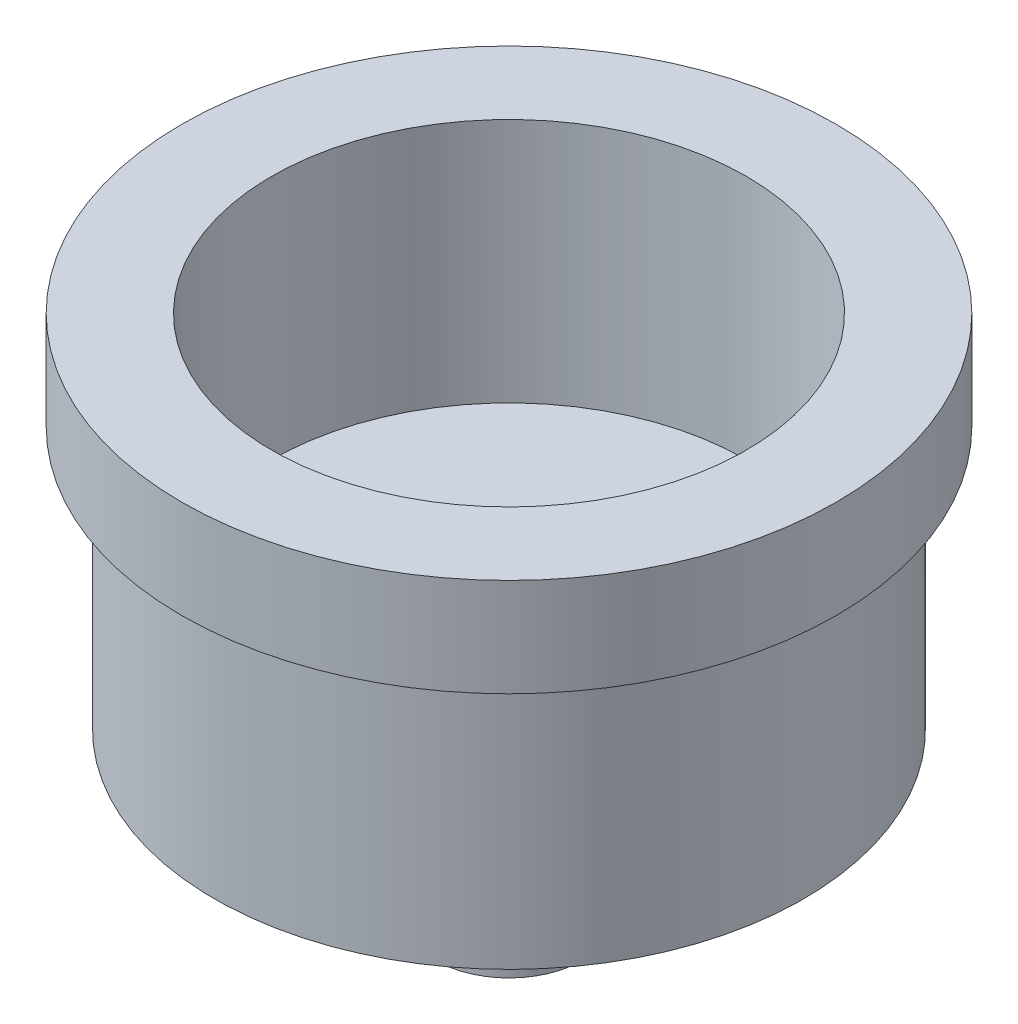
SolidWorks part; units mm, degrees
ref_plane "前视基准面" through (0, 0, 0) normal (0, 0, 1) x (1, 0, 0)
ref_plane "上视基准面" through (0, 0, 0) normal (0, 1, 0) x (1, 0, 0)
ref_plane "右视基准面" through (0, 0, 0) normal (1, 0, 0) x (0, 0, -1)
other "Configuration Table"
sketch "草图1" plane through (0, 0, 0) normal (0, 0, 1) x (1, 0, 0)
  line L0 (0, 0) -> (0, 32) construction
  line L1 (-20, 32) -> (-20, 26)
  line L2 (-20, 26) -> (-18, 26)
  line L3 (-18, 26) -> (-18, 10)
  line L4 (-18, 10) -> (-6.5, 10)
  line L5 (-6.5, 10) -> (-6.5, 9)
  line L6 (-6.5, 9) -> (-4.5, 9)
  line L7 (-4.5, 9) -> (-4.5, 0)
  line L8 (-4.5, 0) -> (-2.5, 0)
  line L9 (-2.5, 0) -> (-2.5, 13)
  line L10 (-2.5, 13) -> (-4.75, 13)
  line L11 (-4.75, 13) -> (-4.75, 17)
  line L12 (-4.75, 17) -> (-14.5, 17)
  line L13 (-14.5, 17) -> (-14.5, 32)
  line L14 (-14.5, 32) -> (-20, 32)
  line L15 (0, 0) -> (-2.5, 0) construction
  point P13 (-5.5, 9)
  dimension "D1" = 40
  dimension "D2" = 6
  dimension "D3" = 36
  dimension "D4" = 15
  dimension "D5" = 29
  dimension "D6" = 5
  dimension "D7" = 9
  dimension "D8" = 9
  dimension "D9" = 2
  dimension "D10" = 9.5
  dimension "D11" = 1
  dimension "D12" = 4
  dimension "D13" = 4
revolve "旋转1" add sketch "草图1" angle 360 about L0
